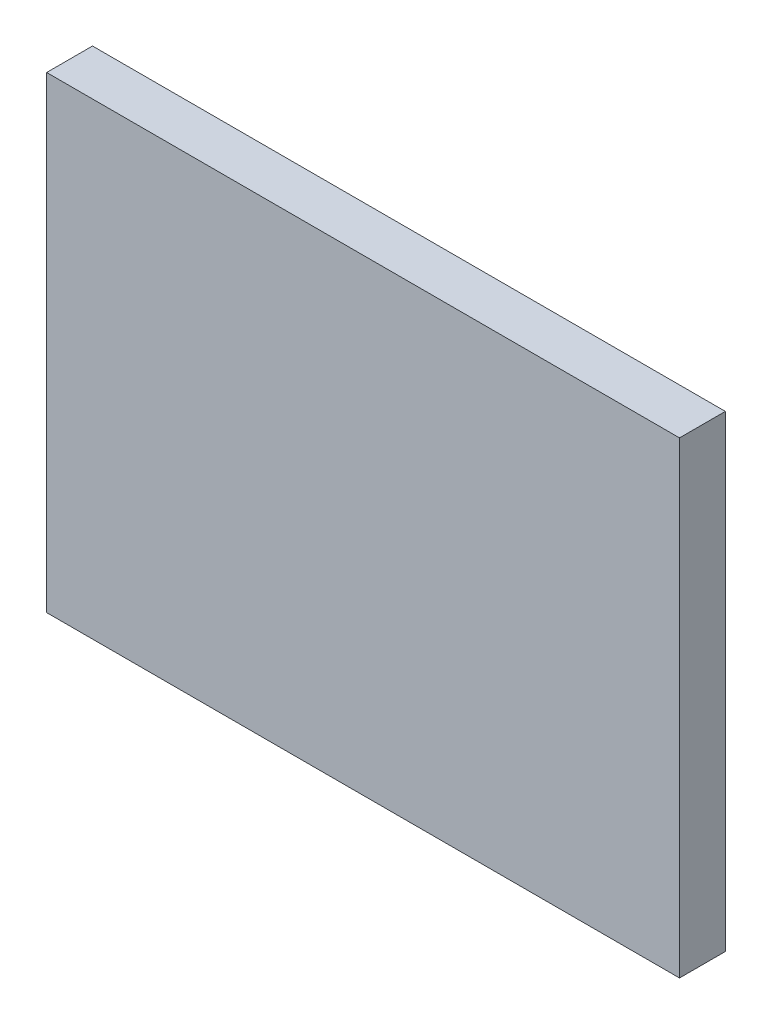
SolidWorks part; units mm, degrees
ref_plane "Plan de face" through (0, 0, 0) normal (0, 0, 1) x (1, 0, 0)
ref_plane "Plan de dessus" through (0, 0, 0) normal (0, 1, 0) x (1, 0, 0)
ref_plane "Plan de droite" through (0, 0, 0) normal (1, 0, 0) x (0, 0, -1)
sketch "Esquisse1" plane through (0, 0, 0) normal (0, 0, 1) x (1, 0, 0)
  line L0 (-41.3958, 20.2654) -> (27.6042, 20.2654)
  line L2 (-41.3958, 20.2654) -> (-41.3958, -30.7346)
  line L3 (-41.3958, -30.7346) -> (27.6042, -30.7346)
  line L4 (27.6042, 20.2654) -> (27.6042, -30.7346)
  dimension "D1" = 69
  dimension "D2" = 51
extrude "Extrusion1" add sketch "Esquisse1" along normal blind 5
